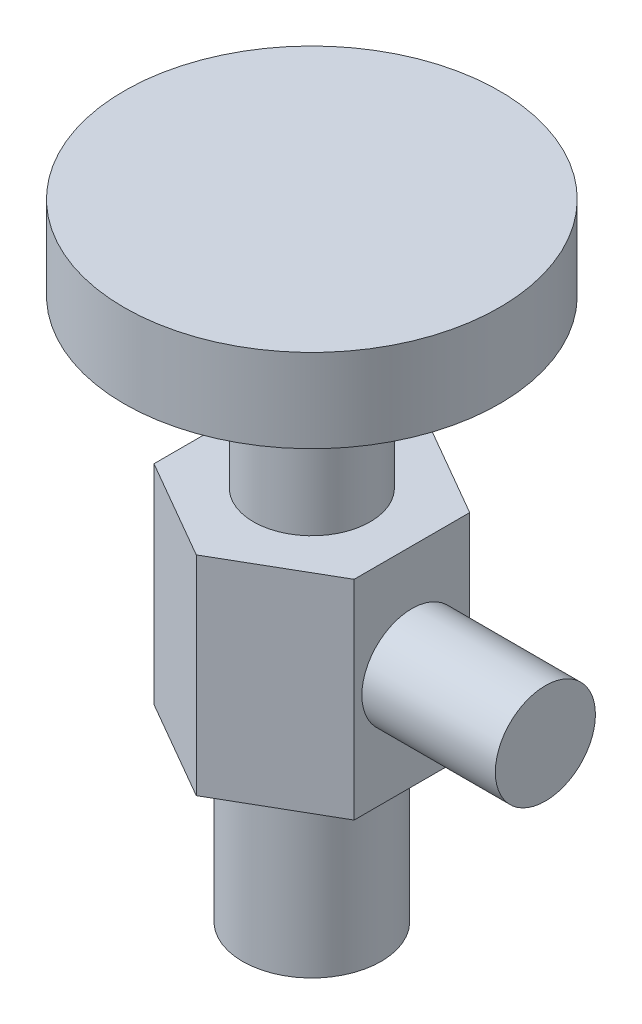
SolidWorks part; units mm, degrees
ref_plane "Front Plane" through (0, 0, 0) normal (0, 0, 1) x (1, 0, 0)
ref_plane "Top Plane" through (0, 0, 0) normal (0, 1, 0) x (1, 0, 0)
ref_plane "Right Plane" through (0, 0, 0) normal (1, 0, 0) x (0, 0, -1)
sketch "Sketch1" plane through (0, 0, 0) normal (0, 1, 0) x (1, 0, 0)
  circle A0 centre (0, 0) radius 8.3
extrude "Boss-Extrude1" add sketch "Sketch1" against normal blind 20
sketch "Sketch2" plane through (0, 0, 0) normal (0, 1, 0) x (1, 0, 0)
  line L1 (0, 13.8564) -> (-12, 6.9282)
  line L2 (-12, 6.9282) -> (-12, -6.9282)
  line L3 (-12, -6.9282) -> (0, -13.8564)
  line L4 (0, -13.8564) -> (12, -6.9282)
  line L5 (12, -6.9282) -> (12, 6.9282)
  line L6 (12, 6.9282) -> (0, 13.8564)
  circle A0 centre (0, 0) radius 12 construction
extrude "Boss-Extrude2" add sketch "Sketch2" along normal blind 25
sketch "Sketch3" plane through (0, 25, 0) normal (0, 1, 0) x (1, 0, 0)
  circle A0 centre (0, 0) radius 7
extrude "Boss-Extrude3" add sketch "Sketch3" along normal blind 20
sketch "Sketch4" plane through (0, 45, 0) normal (0, 1, 0) x (1, 0, 0)
  circle A0 centre (0, 0) radius 22.5
extrude "Boss-Extrude4" add sketch "Sketch4" along normal blind 10
sketch "Sketch5" plane through (0, 0, 0) normal (1, 0, 0) x (0, 0, -1)
  circle A0 centre (0, 12.5) radius 6
extrude "Boss-Extrude5" add sketch "Sketch5" along normal blind 28
